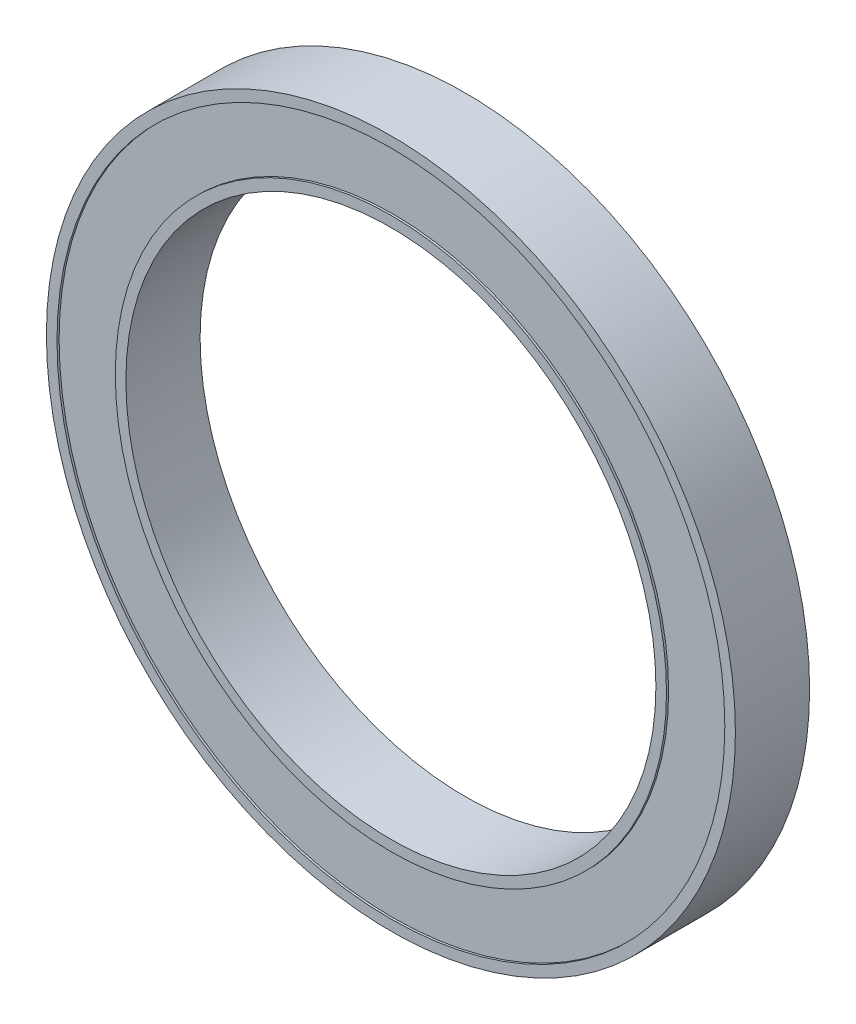
SolidWorks part; units mm, degrees
ref_plane "Front Plane" through (0, 0, 0) normal (0, 0, 1) x (1, 0, 0)
ref_plane "Top Plane" through (0, 0, 0) normal (0, 1, 0) x (1, 0, 0)
ref_plane "Right Plane" through (0, 0, 0) normal (1, 0, 0) x (0, 0, -1)
ref_plane "Plane1"
sketch "Sketch1" plane through (0, 0, 0) normal (0, 0, 1) x (1, 0, 0)
  circle A0 centre (0, 0) radius 32.5
  circle A1 centre (0, 0) radius 31.5
  circle A2 centre (0, 0) radius 26
  circle A3 centre (0, 0) radius 25
  dimension "D1" = 65
  dimension "D2" = 50
extrude "Extrusion1" add sketch "Sketch1" along normal blind 7 contours A2 A3 | A0 A1
ref_plane "Plane2"
sketch "Sketch2" plane through (0, 0, 0.2) normal (0, 0, 1) x (1, 0, 0)
  circle A0 centre (0, 0) radius 31.5
  circle A1 centre (0, 0) radius 26
extrude "Extrusion2" add sketch "Sketch2" along normal blind 6.6 contours A0 A1
